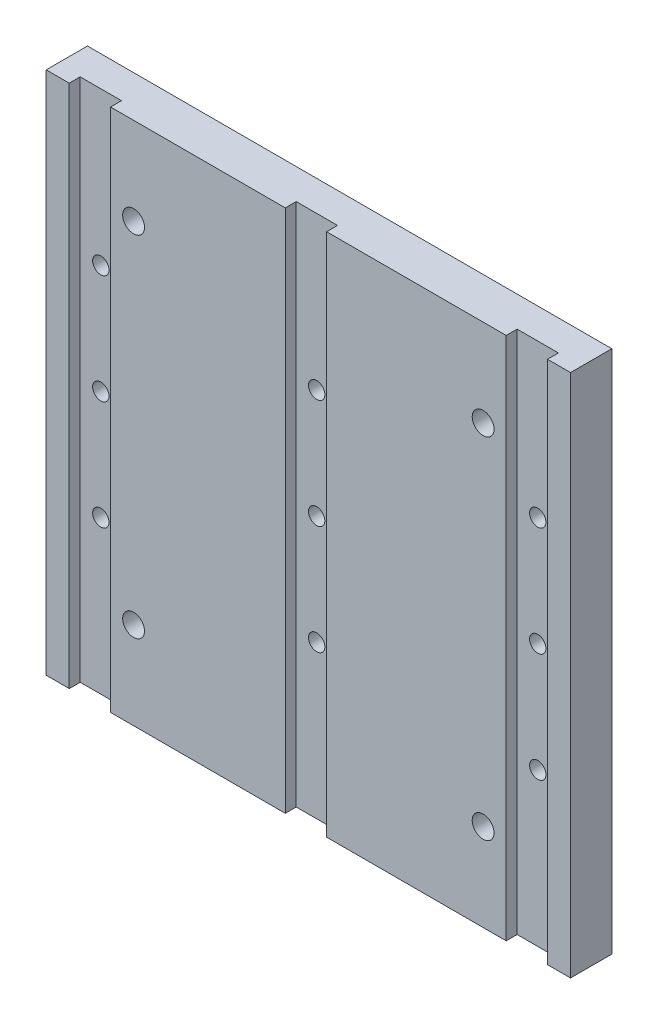
SolidWorks part; units mm, degrees
material "Acrylic (Medium-high impact)"
ref_plane "Front Plane" through (0, 0, 0) normal (0, 0, 1) x (1, 0, 0)
ref_plane "Top Plane" through (0, 0, 0) normal (0, 1, 0) x (1, 0, 0)
ref_plane "Right Plane" through (0, 0, 0) normal (1, 0, 0) x (0, 0, -1)
sketch "Sketch1" plane through (0, 0, 0) normal (0, 0, 1) x (1, 0, 0)
  line L1 (-76.2, 76.2) -> (76.2, 76.2)
  line L2 (-76.2, 76.2) -> (-76.2, -76.2)
  line L3 (-76.2, -76.2) -> (76.2, -76.2)
  line L4 (76.2, 76.2) -> (76.2, -76.2)
  line L5 (-76.2, 76.2) -> (76.2, -76.2) construction
  line L6 (-76.2, -76.2) -> (76.2, 76.2) construction
  circle A0 centre (-50.8, 50.8) radius 3.175
  circle A1 centre (50.8, 50.8) radius 3.175
  circle A2 centre (50.8, -50.8) radius 3.175
  circle A3 centre (-50.8, -50.8) radius 3.175
  point P0 (0, 0)
  dimension "D9" = 6.35
  dimension "D10" = 6.35
  dimension "D13" = 6.35
  dimension "D14" = 6.35
  dimension "D1" = 0
  dimension "D2" = 0
  dimension "D3" = 152.4
  dimension "D4" = 152.4
  dimension "D5" = 25.4
  dimension "D6" = 25.4
  dimension "D7" = 25.4
  dimension "D8" = 25.4
  dimension "D11" = 25.4
  dimension "D12" = 25.4
  dimension "D15" = 25.4
  dimension "D16" = 25.4
extrude "Boss-Extrude1" add sketch "Sketch1" along normal blind 12
sketch "Sketch2" plane through (0, 0, 12) normal (0, 0, 1) x (1, 0, 0)
  line L0 (-76.2, -76.2) -> (76.2, -76.2) construction
  line L1 (-69.5, 76.2) -> (-57.5, 76.2)
  line L2 (-69.5, 76.2) -> (-69.5, -76.2)
  line L3 (-69.5, -76.2) -> (-57.5, -76.2)
  line L4 (-57.5, 76.2) -> (-57.5, -76.2)
  line L5 (-69.5, 76.2) -> (-57.5, -76.2) construction
  line L6 (-69.5, -76.2) -> (-57.5, 76.2) construction
  line L7 (-6.7, 76.2) -> (5.3, 76.2)
  line L8 (-6.7, 76.2) -> (-6.7, -76.2)
  line L9 (-6.7, -76.2) -> (5.3, -76.2)
  line L10 (5.3, 76.2) -> (5.3, -76.2)
  line L11 (-6.7, 76.2) -> (5.3, -76.2) construction
  line L12 (-6.7, -76.2) -> (5.3, 76.2) construction
  line L13 (57.5, 76.2) -> (69.5, 76.2)
  line L14 (57.5, 76.2) -> (57.5, -76.2)
  line L15 (57.5, -76.2) -> (69.5, -76.2)
  line L16 (69.5, 76.2) -> (69.5, -76.2)
  line L17 (57.5, 76.2) -> (69.5, -76.2) construction
  line L18 (57.5, -76.2) -> (69.5, 76.2) construction
  line L19 (-76.2, 76.2) -> (-76.2, -76.2) construction
  line L20 (76.2, -76.2) -> (76.2, 76.2) construction
  point P0 (-63.5, 0)
  point P5 (-0.7, 0)
  point P10 (63.5, 0)
  dimension "D1" = 12
  dimension "D2" = 0
  dimension "D3" = 152.4
  dimension "D4" = 12.7
  dimension "D5" = 0
  dimension "D6" = 12
  dimension "D7" = 152.4
  dimension "D8" = 50.8
  dimension "D9" = 0
  dimension "D10" = 12
  dimension "D11" = 152.4
  dimension "D12" = 12.7
extrude "Cut-Extrude1" cut sketch "Sketch2" against normal blind 3.175
sketch "Sketch3" plane through (0, 0, 8.825) normal (0, 0, 1) x (1, 0, 0)
  line L0 (-63.5, 0) -> (-63.5, 31.75) construction
  line L1 (-63.5, 0) -> (-63.5, -31.75) construction
  line L2 (-69.5, 0) -> (-57.5, 0) construction
  line L3 (-69.5, 76.2) -> (-69.5, -76.2) construction
  line L4 (-57.5, -76.2) -> (-57.5, 76.2) construction
  line L5 (-67.4717, 76.2) -> (-67.4717, -76.2) construction
  line L6 (-57.5, 76.2) -> (-69.5, 76.2) construction
  line L7 (-69.5, -76.2) -> (-57.5, -76.2) construction
  circle A0 centre (-63.5, 0) radius 2.3812
  circle A1 centre (-63.5, 31.75) radius 2.3812
  circle A2 centre (-63.5, -31.75) radius 2.3812
  point P14 (-67.4717, 0)
  point P16 (-63.5, 0)
  dimension "D2" = 4.7625
  dimension "D1" = 31.75
extrude "Cut-Extrude2" cut sketch "Sketch3" against normal through all
sketch "Sketch4" plane through (0, 0, 0) normal (0, 0, -1) x (-1, 0, 0)
  circle A0 centre (63.5, 31.75) radius 3.9687
  circle A1 centre (63.5, 0) radius 3.9687
  circle A2 centre (63.5, -31.75) radius 3.9687
  dimension "D1" = 7.9375
extrude "Cut-Extrude3" cut sketch "Sketch4" against normal blind 5.08
pattern_linear "LPattern1" count 2 spacing 62.738 along (1, 0, 0) of "Cut-Extrude2", "Cut-Extrude3"
pattern_linear "LPattern2" count 2 spacing 127 along (1, 0, 0) of "Cut-Extrude3", "Cut-Extrude2"
